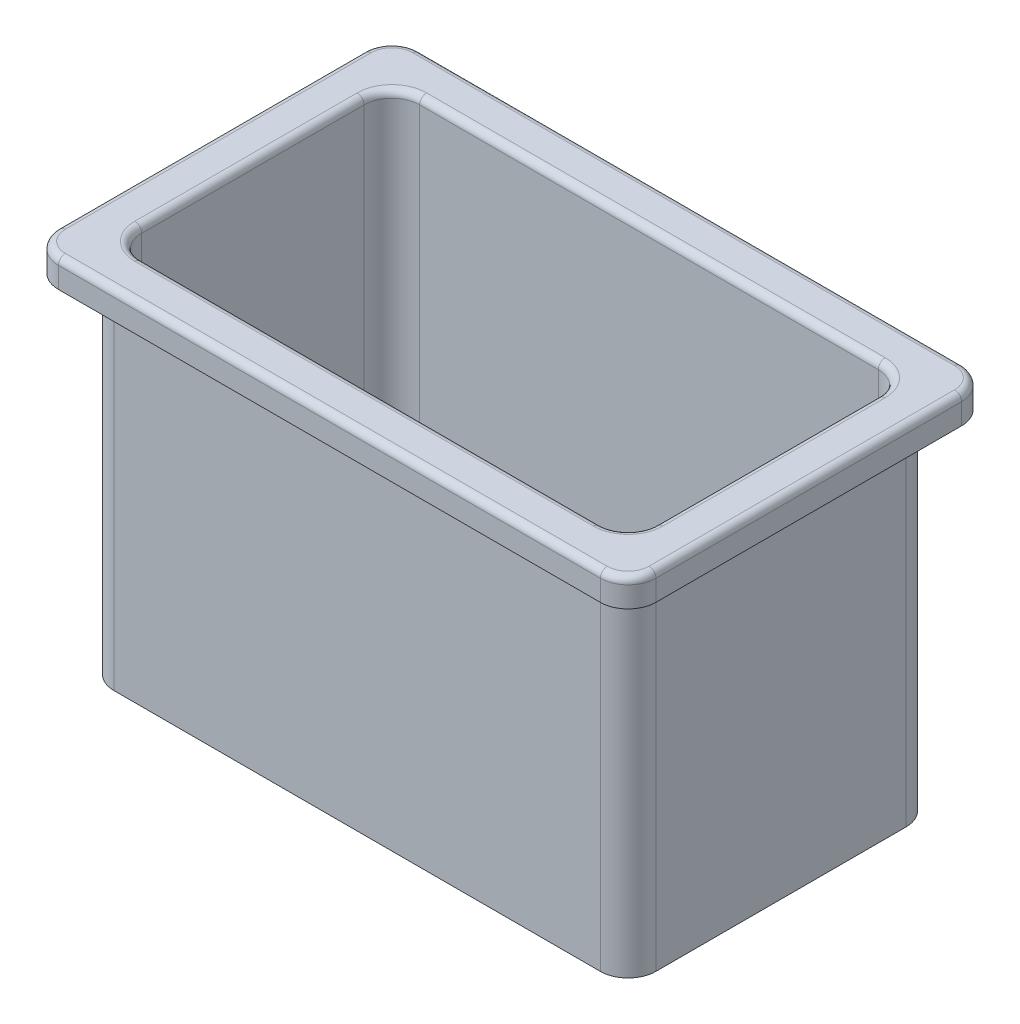
SolidWorks part; units mm, degrees
material "ABS"
ref_plane "Front Plane" through (0, 0, 0) normal (0, 0, 1) x (1, 0, 0)
ref_plane "Top Plane" through (0, 0, 0) normal (0, 1, 0) x (1, 0, 0)
ref_plane "Right Plane" through (0, 0, 0) normal (1, 0, 0) x (0, 0, -1)
sketch "Sketch1" plane through (0, 0, 0) normal (0, 1, 0) x (1, 0, 0)
  line L0 (0, 0) -> (-79633.4309, 0) construction
  line L1 (0, 0) -> (0, -79633.4309) construction
  line L3 (-175, 110) -> (175, 110)
  line L4 (-195, 90) -> (-195, -90)
  line L5 (-175, -110) -> (175, -110)
  line L6 (195, 90) -> (195, -90)
  line L7 (0, -110) -> (0, 110) construction
  line L8 (-195, 0) -> (195, 0) construction
  arc A0 (-195, -90) -> (-175, -110) centre (-175, -90) ccw
  arc A1 (175, -110) -> (195, -90) centre (175, -90) ccw
  arc A2 (175, 110) -> (195, 90) centre (175, 90) cw
  arc A3 (-175, 110) -> (-195, 90) centre (-175, 90) ccw
  point P5 (0, 0)
  point P11 (-195, -110)
  point P14 (195, -110)
  point P20 (-195, 110)
  dimension "D3" = 20
  dimension "D1" = 390
  dimension "D2" = 220
extrude "Boss-Extrude1" add sketch "Sketch1" along normal blind 250
sketch "Sketch3" plane through (0, 0, 0) normal (0, -1, 0) x (1, 0, 0)
  line L0 (0, 0) -> (-50000, 0) construction
  line L1 (0, 0) -> (0, 50000) construction
  line L2 (-173.9486, -97.8864) -> (-181.858, -90.7614)
  line L3 (165, 100) -> (-165, 100)
  line L4 (185, 80) -> (185, -80)
  line L5 (165, -100) -> (-165, -100)
  line L6 (-185, 80) -> (-185, -80)
  line L7 (0, -100) -> (0, 100) construction
  line L8 (185, 0) -> (-185, 0) construction
  line L9 (-173.9486, -97.8864) -> (181.858, 90.7614)
  line L10 (-181.858, -90.7614) -> (173.9486, 97.8864)
  line L11 (181.858, 90.7614) -> (173.9486, 97.8864)
  line L12 (173.9486, -97.8864) -> (181.858, -90.7614)
  line L13 (173.9486, -97.8864) -> (-181.858, 90.7614)
  line L14 (181.858, -90.7614) -> (-173.9486, 97.8864)
  line L15 (-181.858, 90.7614) -> (-173.9486, 97.8864)
  arc A0 (-165, -100) -> (-185, -80) centre (-165, -80) cw
  arc A1 (185, -80) -> (165, -100) centre (165, -80) cw
  arc A2 (165, 100) -> (185, 80) centre (165, 80) cw
  arc A3 (-165, 100) -> (-185, 80) centre (-165, 80) ccw
  point P5 (0, 0)
  point P11 (-185, -100)
  point P14 (185, -100)
  point P19 (-185, 100)
  dimension "D3" = 20
  dimension "D1" = 370
  dimension "D2" = 200
  dimension "D4" = 10
  dimension "D5" = 10
  dimension "D6" = 402.7236
  dimension "D7" = 402.7236
extrude "Cut-Extrude3" cut sketch "Sketch3" against normal blind 10 contours A1 L13 L9 A0 L5 | L13 A3 L6 A0 L10 | L3 A3 L14 L10 A2 | A2 L9 L14 A1 L4
sketch "Sketch5" plane through (0, 250, 0) normal (0, 1, 0) x (1, 0, 0)
  line L0 (0, 0) -> (-50000, 0) construction
  line L1 (0, 0) -> (0, 50000) construction
  line L3 (195, 130) -> (-195, 130)
  line L4 (215, 110) -> (215, -110)
  line L5 (195, -130) -> (-195, -130)
  line L6 (-215, 110) -> (-215, -110)
  line L7 (0, -130) -> (0, 130) construction
  line L8 (215, 0) -> (-215, 0) construction
  arc A0 (-195, -130) -> (-215, -110) centre (-195, -110) cw
  arc A1 (215, -110) -> (195, -130) centre (195, -110) cw
  arc A2 (195, 130) -> (215, 110) centre (195, 110) cw
  arc A3 (-195, 130) -> (-215, 110) centre (-195, 110) ccw
  point P5 (0, 0)
  point P11 (-215, -130)
  point P14 (215, -130)
  point P19 (-215, 130)
  dimension "D3" = 20
  dimension "D1" = 430
  dimension "D2" = 260
extrude "Boss-Extrude2" add sketch "Sketch5" along normal blind 20
sketch "Sketch6" plane through (0, 270, 0) normal (0, 1, 0) x (1, 0, 0)
  line L0 (0, 0) -> (-50000, 0) construction
  line L1 (0, 0) -> (0, 50000) construction
  line L3 (-165, -100) -> (165, -100)
  line L4 (-185, -80) -> (-185, 80)
  line L5 (-165, 100) -> (165, 100)
  line L6 (185, -80) -> (185, 80)
  line L7 (0, 100) -> (0, -100) construction
  line L8 (-185, 0) -> (185, 0) construction
  arc A0 (165, 100) -> (185, 80) centre (165, 80) cw
  arc A1 (165, -100) -> (185, -80) centre (165, -80) ccw
  arc A2 (-165, -100) -> (-185, -80) centre (-165, -80) cw
  arc A3 (-185, 80) -> (-165, 100) centre (-165, 80) cw
  point P5 (0, 0)
  point P13 (185, -100)
  point P17 (-185, -100)
  point P20 (-185, 100)
  dimension "D3" = 20
  dimension "D1" = 370
  dimension "D2" = 200
extrude "Cut-Extrude4" cut sketch "Sketch6" against normal blind 240
fillet "Fillet1" radius 5 8 edges at (-179.1421, 270, -94.1421) (0, 270, -100) (179.1421, 270, -94.1421) (185, 270, 0) (179.1421, 270, 94.1421) (0, 270, 100) (-179.1421, 270, 94.1421) (-185, 270, 0)
fillet "Fillet2" radius 5 8 edges at (-209.1421, 270, -124.1421) (0, 270, -130) (209.1421, 270, -124.1421) (215, 270, 0) (209.1421, 270, 124.1421) (0, 270, 130) (-209.1421, 270, 124.1421) (-215, 270, 0)
